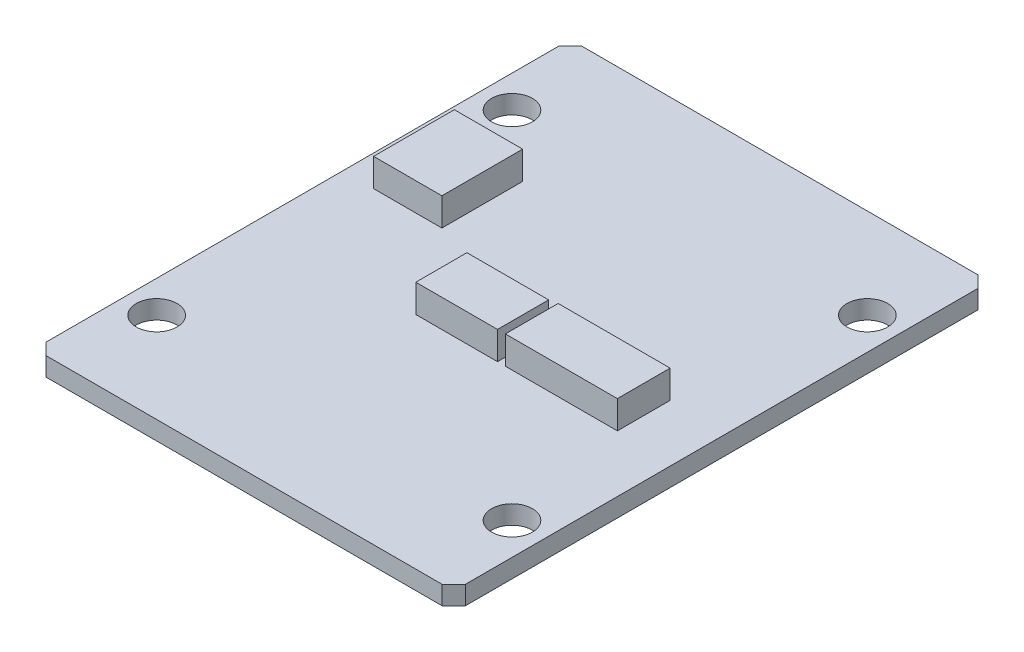
SolidWorks part; units mm, degrees
ref_plane "Front Plane" through (0, 0, 0) normal (0, 0, 1) x (1, 0, 0)
ref_plane "Top Plane" through (0, 0, 0) normal (0, 1, 0) x (1, 0, 0)
ref_plane "Right Plane" through (0, 0, 0) normal (1, 0, 0) x (0, 0, -1)
sketch "Sketch1" plane through (0, 0, 0) normal (0, 1, 0) x (1, 0, 0)
  line L0 (0, 18) -> (0, -18) construction
  line L1 (-18, 23) -> (18, 23)
  line L2 (-18, 23) -> (-18, -23)
  line L3 (-18, -23) -> (18, -23)
  line L4 (18, 23) -> (18, -23)
  line L5 (-18, 23) -> (18, -23) construction
  line L6 (-18, -23) -> (18, 23) construction
  line L7 (18, -18) -> (-18, -18)
  line L8 (18, -18) -> (18, 18)
  line L9 (18, 18) -> (-18, 18)
  line L10 (-18, -18) -> (-18, 18)
  line L11 (18, -18) -> (-18, 18) construction
  line L12 (18, 18) -> (-18, -18) construction
  line L13 (-18, 0) -> (18, 0) construction
  circle A0 centre (-15.25, 15.25) radius 1.75
  circle A1 centre (15.25, 15.25) radius 1.75
  circle A2 centre (-15.25, -15.25) radius 1.75
  circle A3 centre (15.25, -15.25) radius 1.75
  point P0 (0, 0)
  point P6 (0, 0)
  dimension "D3" = 3.5
  dimension "D1" = 46
  dimension "D2" = 36
  dimension "D4" = 30.5
extrude "PCB" add sketch "Sketch1" along normal blind 1.6 contours L9 L4 L1 L2 | L4 L9 L2 L7 A3 A1 A0 A2 | L4 L7 L2 L3
sketch "Sketch2" plane through (0, 1.6, 0) normal (0, 1, 0) x (1, 0, 0)
  line L1 (13.118, 0.4566) -> (3.5041, 0.4566)
  line L2 (13.118, 0.4566) -> (13.118, -4.0741)
  line L3 (13.118, -4.0741) -> (3.5041, -4.0741)
  line L4 (3.5041, 0.4566) -> (3.5041, -4.0741)
  line L5 (2.8313, 0.3154) -> (-4.1847, 0.3154)
  line L6 (2.8313, 0.3154) -> (2.8313, -4.0741)
  line L7 (2.8313, -4.0741) -> (-4.1847, -4.0741)
  line L8 (-4.1847, 0.3154) -> (-4.1847, -4.0741)
  line L9 (-15.3548, 10.4054) -> (-9.4909, 10.4054)
  line L10 (-15.3548, 10.4054) -> (-15.3548, 3.472)
  line L11 (-15.3548, 3.472) -> (-9.4909, 3.472)
  line L12 (-9.4909, 10.4054) -> (-9.4909, 3.472)
extrude "Components" add sketch "Sketch2" along normal offset from surface (2.4 mm away) 4 contours L12 L9 L10 L11 | L5 L8 L7 L6 | L1 L4 L3 L2 up to face at (0, 0, 0)
chamfer "Corners" distance 1 angle 45 4 edges at (18, 0.8, 23) (-18, 0.8, 23) (-18, 0.8, -23) (18, 0.8, -23)
